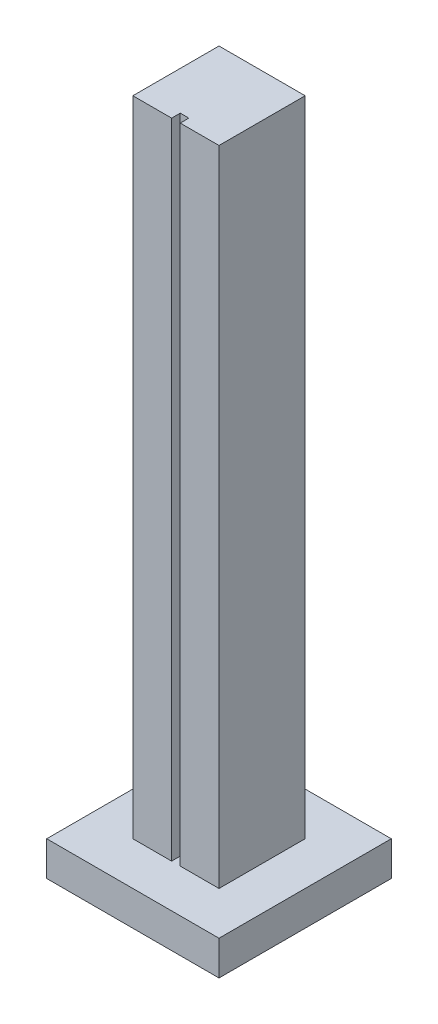
SolidWorks part; units mm, degrees
ref_plane "Front Plane" through (0, 0, 0) normal (0, 0, 1) x (1, 0, 0)
ref_plane "Top Plane" through (0, 0, 0) normal (0, 1, 0) x (1, 0, 0)
ref_plane "Right Plane" through (0, 0, 0) normal (1, 0, 0) x (0, 0, -1)
sketch "Sketch1" plane through (0, 0, 0) normal (0, 1, 0) x (1, 0, 0)
  line L0 (4.5, 0) -> (4.5, 1)
  line L1 (0, 0) -> (4.5, 0)
  line L2 (0, 0) -> (0, 10)
  line L3 (0, 10) -> (10, 10)
  line L4 (10, 0) -> (10, 10)
  line L5 (4.5, 1) -> (5.5, 1)
  line L6 (5.5, 1) -> (5.5, 0)
  line L7 (5.5, 0) -> (10, 0)
  point P7 (5, 1)
  point P10 (5, 10)
  dimension "D1" = 1
  dimension "D2" = 10
  dimension "D3" = 10
  dimension "D4" = 1
extrude "Boss-Extrude1" add sketch "Sketch1" along normal blind 78.7
sketch "Sketch2" plane through (0, 0, 0) normal (0, 1, 0) x (1, 0, 0)
  line L0 (10, 10) -> (0, 10) construction
  line L1 (-5, 15) -> (15, 15)
  line L2 (-5, 15) -> (-5, -5)
  line L3 (-5, -5) -> (15, -5)
  line L4 (15, 15) -> (15, -5)
  line L5 (0, 10) -> (0, 0) construction
  point P6 (5, 10)
  point P7 (5, 15)
  point P10 (0, 5)
  point P11 (-5, 5)
  dimension "D1" = 20
  dimension "D2" = 20
extrude "Boss-Extrude2" add sketch "Sketch2" along normal blind 4
